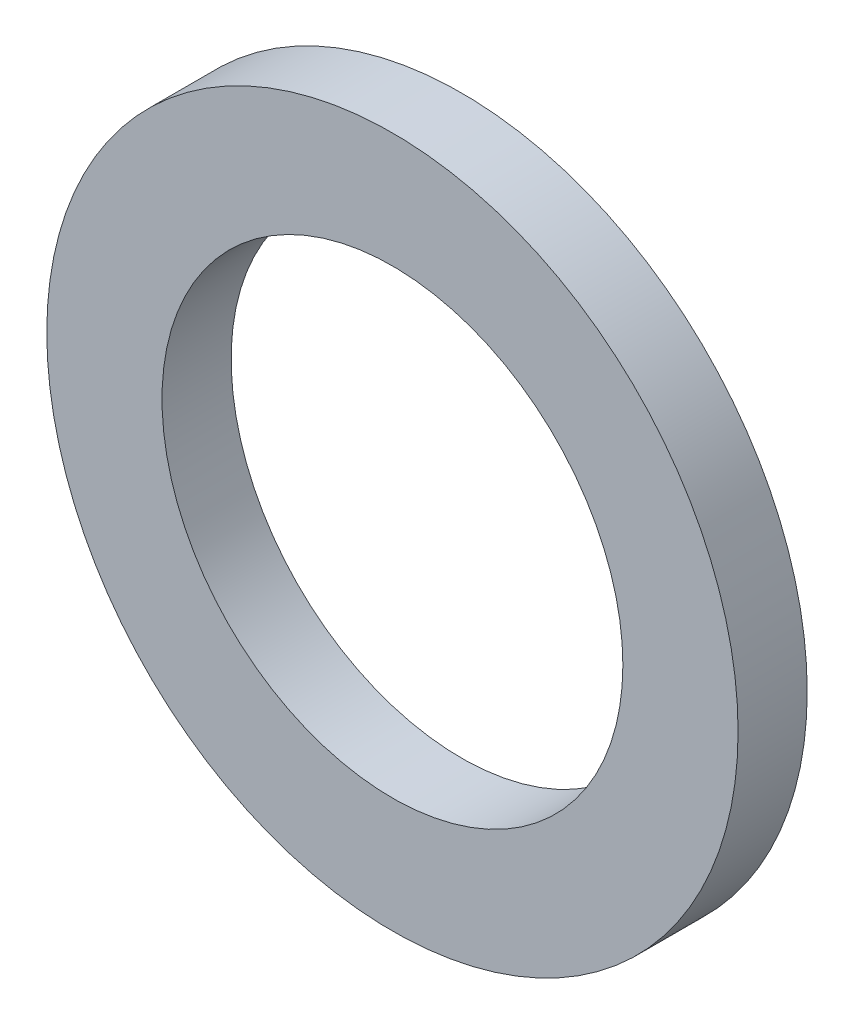
SolidWorks part; units mm, degrees
ref_plane "Plan de face" through (0, 0, 0) normal (0, 0, 1) x (1, 0, 0)
ref_plane "Plan de dessus" through (0, 0, 0) normal (0, 1, 0) x (1, 0, 0)
ref_plane "Plan de droite" through (0, 0, 0) normal (1, 0, 0) x (0, 0, -1)
sketch "Esquisse1" plane through (0, 0, 0) normal (0, 0, 1) x (1, 0, 0)
  circle A0 centre (0, 0) radius 6
  dimension "D1" = 12
extrude "Boss.-Extru.1" add sketch "Esquisse1" along normal blind 1.2
sketch "Esquisse2" plane through (0, 0, 1.2) normal (0, 0, 1) x (1, 0, 0)
  circle A0 centre (0, 0) radius 4
  dimension "D1" = 8
extrude "Enlèv. mat.-Extru.1" cut sketch "Esquisse2" against normal blind 1.2
